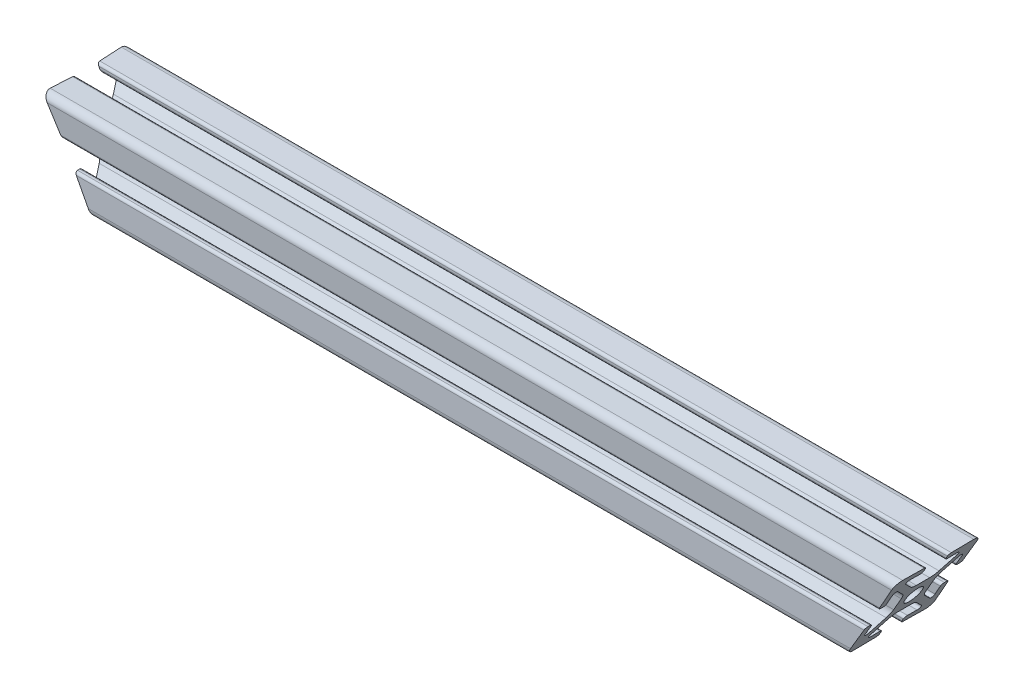
SolidWorks part; units mm, degrees
material "6061-T6 (SS)"
ref_plane "Front Plane" through (0, 0, 0) normal (0, 0, 1) x (1, 0, 0)
ref_plane "Top Plane" through (0, 0, 0) normal (0, 1, 0) x (1, 0, 0)
ref_plane "Right Plane" through (0, 0, 0) normal (1, 0, 0) x (0, 0, -1)
sketch "Sketch1" plane through (0, 0, 0) normal (1, 0, 0) x (0, 0, -1)
  line L0 (0, -12.7) -> (0, 12.7) construction
  line L1 (-7.874, 12.7) -> (7.874, 12.7) construction
  line L2 (-12.7, 0) -> (12.7, 0) construction
  line L3 (-7.874, 12.7) -> (-7.874, 4.826) construction
  line L4 (-3.302, 12.7) -> (3.302, 12.7) construction
  line L5 (-12.7, -12.7) -> (12.7, -12.7) construction
  line L6 (-12.7, 12.7) -> (12.7, 12.7) construction
  circle A0 centre (0, 0) radius 2.54 construction
  point P7 (0, 12.7)
  point P10 (0, 0)
  point P13 (0, 0)
  point P16 (0, 12.7)
  point P17 (-3.302, 12.7)
  point P18 (3.302, 12.7)
  point P21 (0, -12.7)
  point P24 (0, 12.7)
  dimension "Center Hole Diameter" = 5.08
  dimension "Rail Width" = 25.4
  dimension "Rail Height" = 25.4
  dimension "T-Slot Depth" = 7.874
  dimension "D1" = 15.748
  dimension "T-Slot Width" = 6.604
  dimension "D2" = 12.7
sketch "Sketch2" plane through (0, 0, 0) normal (0, 0, 1) x (1, 0, 0)
  line L0 (-127, 0) -> (127, 0) construction
  line L1 (0, 0) -> (0, 26.104) construction
  line L2 (127, -12.7) -> (127, 12.7) construction
  line L3 (-127, -12.7) -> (-127, 12.7) construction
  point P3 (-88.9, 0)
  point P8 (0, 0)
  point P9 (88.9, 0)
  point P12 (127, 0)
  point P15 (-127, 0)
  dimension "Length" = 254
  dimension "D1" = 38.1
  dimension "D2" = 25.4
sketch "Sketch3" plane through (0, 0, 0) normal (1, 0, 0) x (0, 0, -1)
  line L0 (0, 4.826) -> (1.9842, 4.826)
  line L1 (0, -12.7) -> (0, 12.7) construction
  line L2 (4.2293, 5.7559) -> (7.5866, 9.1132)
  line L6 (7.0212, 10.4136) -> (4.0906, 10.3112)
  line L7 (3.302, 11.0728) -> (3.302, 11.7082)
  line L8 (-7.874, 12.7) -> (7.874, 12.7) construction
  line L10 (0, 0) -> (12.7, 12.7) construction
  line L13 (0, 4.826) -> (0, 2.54)
  line L14 (4.826, 0) -> (2.54, 0)
  line L31 (4.826, 0) -> (4.826, 1.9842)
  line L32 (4.0374, 12.4697) -> (10.5971, 12.6988)
  line L33 (-12.7, 0) -> (12.7, 0) construction
  line L34 (-12.7, 12.7) -> (12.7, 12.7) construction
  line L35 (5.7559, 4.2293) -> (9.1132, 7.5866)
  line L36 (0, 12.7) -> (12.7, 12.7) construction
  line L37 (12.7, 12.7) -> (12.7, 8.0234) construction
  line L38 (11.0728, 3.302) -> (11.7082, 3.302)
  line L39 (10.4136, 7.0212) -> (10.3112, 4.0906)
  line L40 (12.6988, 10.5971) -> (12.4697, 4.0374)
  arc A0 (2.54, 0) -> (0, 2.54) centre (0, 0) ccw
  arc A1 (1.9842, 4.826) -> (4.2293, 5.7559) centre (1.9842, 8.001) ccw
  circle A2 centre (0, 0) radius 2.54 construction
  arc A7 (3.302, 11.7082) -> (4.0374, 12.4697) centre (4.064, 11.7082) cw
  arc A8 (4.0906, 10.3112) -> (3.302, 11.0728) centre (4.064, 11.0728) cw
  arc A14 (4.826, 1.9842) -> (5.7559, 4.2293) centre (8.001, 1.9842) cw
  arc A16 (10.5971, 12.6988) -> (12.6988, 10.5971) centre (10.668, 10.668) cw
  arc A17 (7.0212, 10.4136) -> (7.5866, 9.1132) centre (7.0478, 9.652) cw
  arc A18 (10.4136, 7.0212) -> (9.1132, 7.5866) centre (9.652, 7.0478) ccw
  arc A19 (10.3112, 4.0906) -> (11.0728, 3.302) centre (11.0728, 4.064) ccw
  arc A20 (11.7082, 3.302) -> (12.4697, 4.0374) centre (11.7082, 4.064) ccw
  point P37 (3.2994, 4.826)
  point P49 (12.7, 3.302)
  point P52 (3.302, 12.7)
  point P55 (3.302, 10.2837)
  dimension "D4" = 3.175
  dimension "D9" = 2.159
  dimension "D12" = 0.762
  dimension "D3" = 2.032
  dimension "D8" = 0.762
  dimension "D2" = 45
  dimension "D5" = 2
  dimension "D6" = 45
  dimension "D7" = 2.159
extrude "Boss-Extrude1" add sketch "Sketch3" against normal up to vertex (127 mm away) and the other way up to vertex (127 mm away) up to point (-127, 0, 0) other way up to point (127, 0, 0)
mirror "Mirror1" about plane through (0, 0, 0) normal (0, 1, 0) of bodies 104
mirror "Mirror2" about plane through (0, 0, 0) normal (0, 0, 1) of bodies 105
sketch "Sketch4" plane through (0, 0, 0) normal (0, 0, 1) x (1, 0, 0)
  line L1 (-129.54, -38.1) -> (129.54, -38.1)
  line L3 (127, 12.7) -> (112.3353, -12.7)
  line L4 (112.3353, -12.7) -> (-112.3353, -12.7)
  line L5 (-112.3353, -12.7) -> (-127, 12.7)
  line L6 (-127, 12.7) -> (-129.54, 12.7)
  line L7 (-129.54, 12.7) -> (-129.54, -38.1)
  line L8 (127, 12.7) -> (129.54, 12.7)
  line L9 (129.54, 12.7) -> (129.54, -38.1)
  dimension "D2" = 25.4
  dimension "D4" = 25.4
  dimension "D1" = 2.54
  dimension "D3" = 2.54
  dimension "D5" = 30
  dimension "D6" = 30
extrude "Cut-Extrude1" cut sketch "Sketch4" along normal blind 12.7 and the other way blind 12.7 contours L1 L9 L8 L3 L4 L5 L6 L7
ref_plane "Plane1" through (0, -12.6988, 0) normal (0, 1, 0) x (1, 0, 0)
ref_plane "Plane2" through (0, 0, -12.6988) normal (0, 0, -1) x (-1, 0, 0)
ref_plane "Plane3" through (0, 12.6988, 0) normal (0, -1, 0) x (-1, 0, 0)
ref_plane "Plane4" through (0, 0, 12.6988) normal (0, 0, 1) x (1, 0, 0)
equation "\"D1@Sketch2\"=\"Rail Height@Sketch1\"*1.5"
equation "\"D2@Sketch2\"=\"Rail Height@Sketch1\""
equation "\"MaxLength\"= ( \"ROVWidth@Assem2.SLDASM\" - \"FaceWidth@Assem2.SLDASM\" ) / ( 2 * SIN ( \"Phi@Assem2.SLDASM\" ) )"
equation "\"Length@Sketch2\"= \"MaxLength\""
equation "\"LeftCutAngle\"= ( \"Phi@Assem2.SLDASM\" + \"Theta@Assem2.SLDASM\" ) / 2"
equation "\"RightCutAngle\"= 45 - ( \"Phi@Assem2.SLDASM\" / 2 )"
equation "\"BarThickness\"= 1in"
equation "\"InnerLength\"= \"MaxLength\" - TAN ( \"LeftCutAngle\" ) - TAN ( \"RightCutAngle\" )"
equation "\"RightBevelLength\"= tan ( \"RightCutAngle\" )"
equation "\"D2@Sketch4\"=\"BarThickness\""
equation "\"D4@Sketch4\"= \"BarThickness\""
equation "\"D1@Cut-Extrude1\"=\"BarThickness\"/2"
equation "\"D2@Cut-Extrude1\"=\"BarThickness\"/2"
equation "\"D5@Sketch4\"=\"LeftCutAngle\""
equation "\"D6@Sketch4\"=\"RightCutAngle\""
